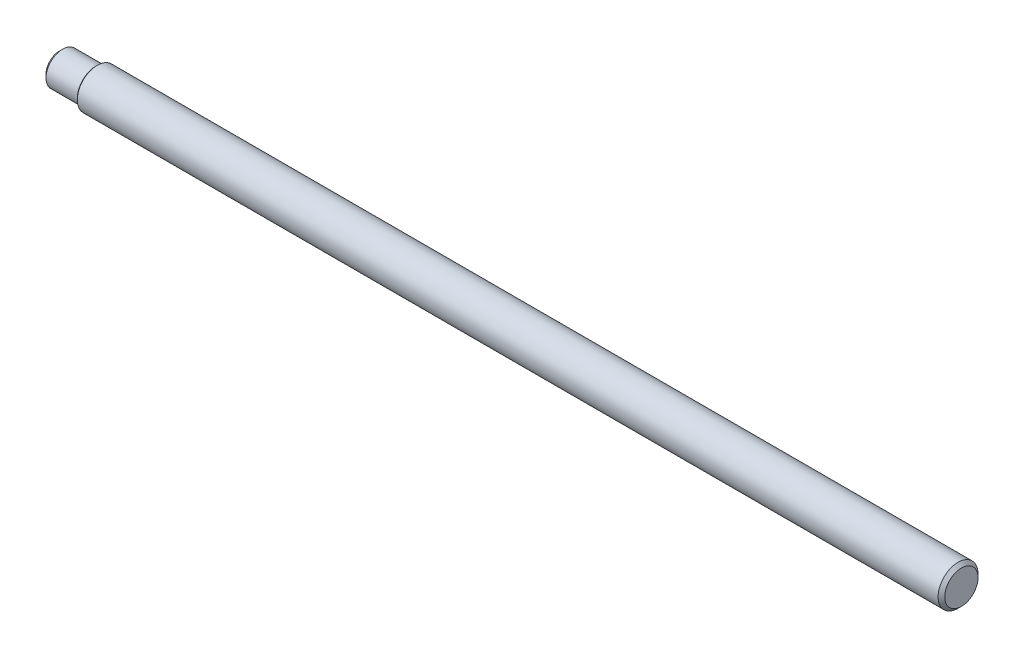
SolidWorks part; units mm, degrees
material "Plain Carbon Steel"
ref_plane "Front Plane" through (0, 0, 0) normal (0, 0, 1) x (1, 0, 0)
ref_plane "Top Plane" through (0, 0, 0) normal (0, 1, 0) x (1, 0, 0)
ref_plane "Right Plane" through (0, 0, 0) normal (1, 0, 0) x (0, 0, -1)
ref_plane "Plane1" through (0, 0, 0) normal (0, 0, 1) x (1, 0, 0)
sketch "Sketch1" plane through (0, 0, 0) normal (0, 0, 1) x (1, 0, 0)
  line L0 (-5.5, 0) -> (-5.5, 2)
  line L1 (-5.5, 2) -> (-5, 2.5)
  line L2 (-5, 2.5) -> (-0.2, 2.5)
  line L3 (0, 2.7) -> (0, 2.8)
  line L4 (0, 2.8) -> (0.2, 3)
  line L5 (0.2, 3) -> (129.5, 3)
  line L6 (129.5, 3) -> (130, 2.5)
  line L7 (130, 2.5) -> (130, 0)
  line L8 (130, 0) -> (-5.5, 0)
  line L9 (130, 0) -> (-5.5, 0) construction
  arc A0 (-0.2, 2.5) -> (0, 2.7) centre (-0.2, 2.7) ccw
revolve "Revolve1" add sketch "Sketch1" angle 360 about L9
